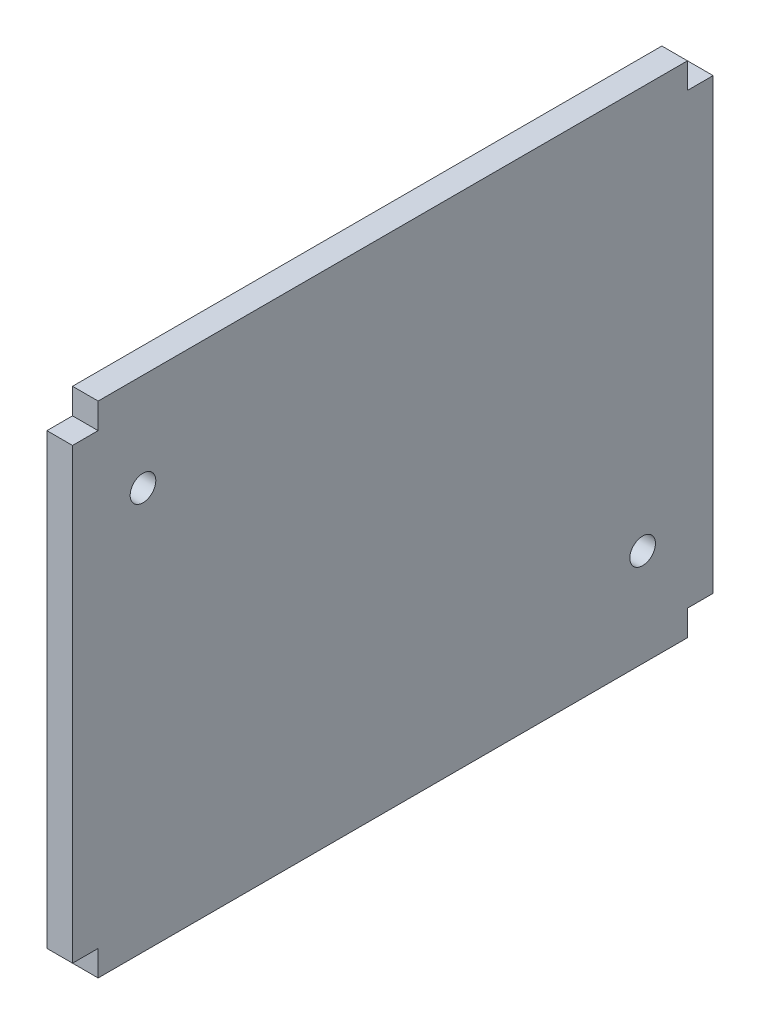
SolidWorks part; units mm, degrees
ref_plane "Front Plane" through (0, 0, 0) normal (0, 0, 1) x (1, 0, 0)
ref_plane "Top Plane" through (0, 0, 0) normal (0, 1, 0) x (1, 0, 0)
ref_plane "Right Plane" through (0, 0, 0) normal (1, 0, 0) x (0, 0, -1)
sketch "Sketch1" plane through (0, 0, 0) normal (1, 0, 0) x (0, 0, -1)
  line L0 (-50, 35) -> (-46, 35)
  line L5 (-50, 35) -> (-50, -35)
  line L6 (-50, 0) -> (50, 0)
  line L7 (-46, 35) -> (-46, 39)
  line L8 (-46, 39) -> (46, 39)
  line L9 (46, 35) -> (46, 39)
  line L10 (50, 35) -> (50, -35)
  line L11 (0, -39) -> (0, 39)
  line L12 (50, 35) -> (46, 35)
  line L13 (50, -35) -> (46, -35)
  line L14 (46, -35) -> (46, -39)
  line L15 (-46, -39) -> (46, -39)
  line L16 (-46, -35) -> (-46, -39)
  line L17 (-50, -35) -> (-46, -35)
  point P1 (0, 0)
  point P16 (0, 0)
  dimension "D1" = 39
  dimension "D2" = 4
  dimension "D3" = 4
  dimension "D4" = 50
extrude "Boss-Extrude1" add sketch "Sketch1" along normal blind 4 contours L6 L11 L8 L7 L0 L5 | L10 L12 L9 L8 L11 L6 | L11 L15 L14 L13 L10 L6 | L5 L17 L16 L15 L11 L6
sketch "Sketch2" plane through (0, 0, 0) normal (-1, 0, 0) x (0, 0, 1)
  line L1 (-39, -23.75) -> (39, -23.75)
  line L2 (-39, -23.75) -> (-39, 23.75)
  line L3 (-39, 23.75) -> (39, 23.75)
  line L4 (39, -23.75) -> (39, 23.75)
  line L5 (-39, -23.75) -> (39, 23.75) construction
  line L6 (-39, 23.75) -> (39, -23.75) construction
  point P0 (0, 0)
  dimension "D1" = 47.5
  dimension "D2" = 78
hole_wizard "Ø4.0mm Dowel Hole1" positions "3DSketch1" profile "Sketch3" hole size "Ø4.0" standard "ISO" end condition through all
sketch3d "3DSketch1"
  point P0 (0, -23.75, -39)
  point P3 (0, 23.75, 39)
sketch "Sketch3" plane through (0, -23.75, -39) normal (0, 1, 0) x (0, 0, 1)
  line L0 (0, 0) -> (0, 4)
  line L1 (0, 4) -> (2, 4)
  line L2 (2, 4) -> (2, 0)
  line L5 (2, 0) -> (0, 0)
  line L11 (0, -6.35) -> (0, 107.95) construction
  dimension "Thru Hole Dia." = 4
  dimension "Thru Hole Depth" = 4
